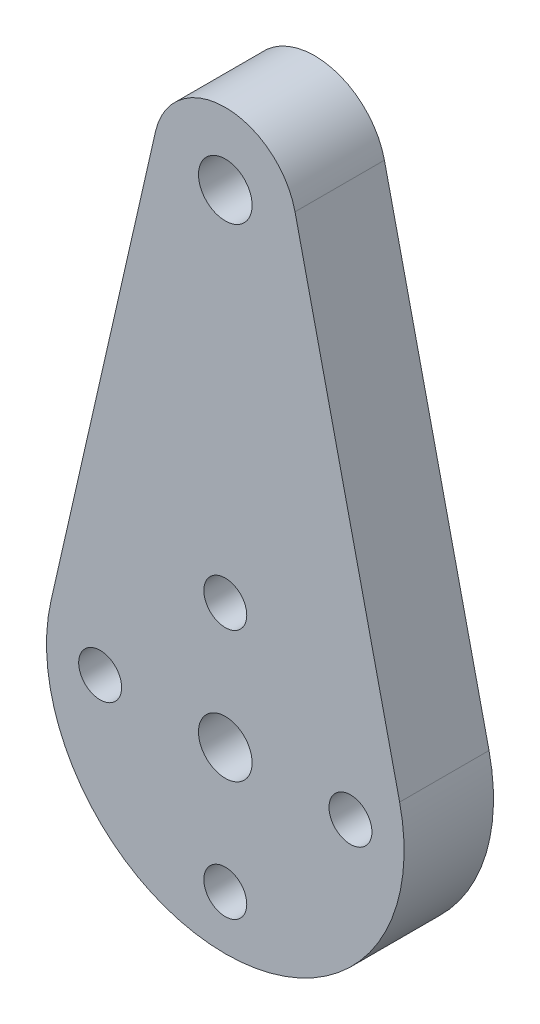
SolidWorks part; units mm, degrees
ref_plane "Ön Düzlem" through (0, 0, 0) normal (0, 0, 1) x (1, 0, 0)
ref_plane "Üst Düzlem" through (0, 0, 0) normal (0, 1, 0) x (1, 0, 0)
ref_plane "Sağ Düzlem" through (0, 0, 0) normal (1, 0, 0) x (0, 0, -1)
sketch "Çizim1" plane through (0, 0, 0) normal (0, 0, 1) x (1, 0, 0)
  line L0 (-9.75, 2.2222) -> (-3.9, 27.8889)
  line L1 (3.9, 27.8889) -> (9.75, 2.2222)
  circle A0 centre (0, 0) radius 10
  circle A1 centre (0, 0) radius 1.5
  circle A2 centre (0, 27) radius 1.5
  circle A3 centre (0, 27) radius 4
  dimension "D1" = 27
  dimension "D2" = 8
  dimension "D3" = 3
  dimension "D4" = 20
  dimension "D5" = 3
extrude "Yükseklik-Ekstrüzyon1" add sketch "Çizim1" along normal blind 5 contours A0 A1 | A3 L0 A0 L1 | A3 A2
sketch "Çizim2" plane through (0, 0, 5) normal (0, 0, 1) x (1, 0, 0)
  circle A6 centre (0, 0) radius 10
  circle A7 centre (0, 0) radius 1.35
  circle A8 centre (0, 7) radius 1.2
  circle A9 centre (7, 0) radius 1.2
  circle A10 centre (0, -7) radius 1.2
  circle A11 centre (-7, 0) radius 1.2
  point P24 (0, 0)
extrude "Kes-Ekstrüzyon1" cut sketch "Çizim2" against normal blind 10 contours A8 | A11 | A10 | A9
